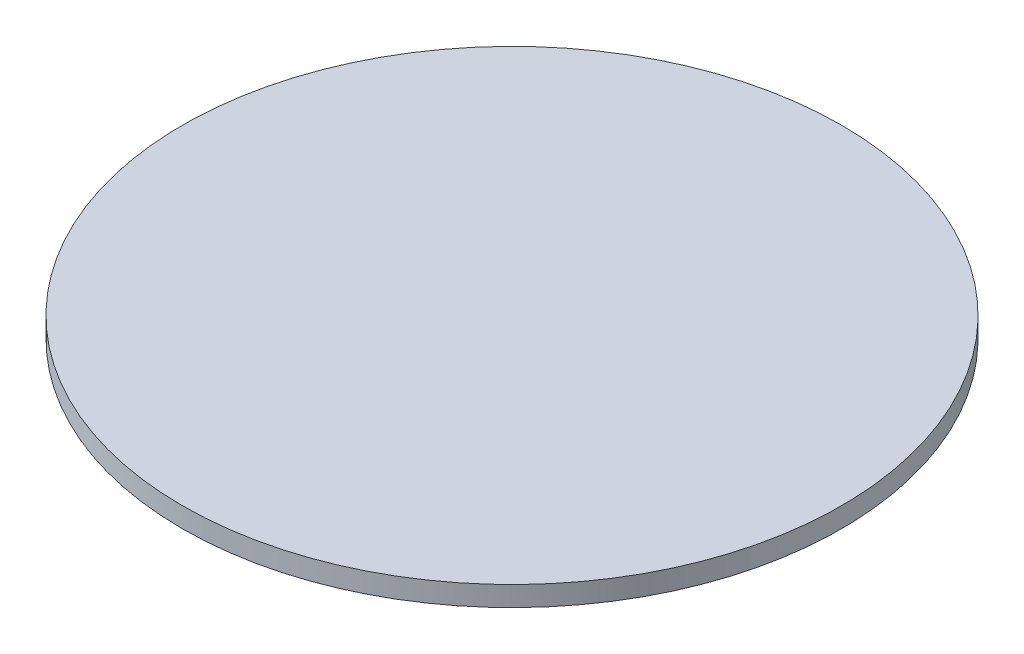
SolidWorks part; units mm, degrees
ref_plane "Front Plane" through (0, 0, 0) normal (0, 0, 1) x (1, 0, 0)
ref_plane "Top Plane" through (0, 0, 0) normal (0, 1, 0) x (1, 0, 0)
ref_plane "Right Plane" through (0, 0, 0) normal (1, 0, 0) x (0, 0, -1)
sketch "Sketch1" plane through (0, 0, 0) normal (0, 1, 0) x (1, 0, 0)
  circle A0 centre (0, 0) radius 41.8568
extrude "Boss-Extrude1" add sketch "Sketch1" along normal blind 2.54
